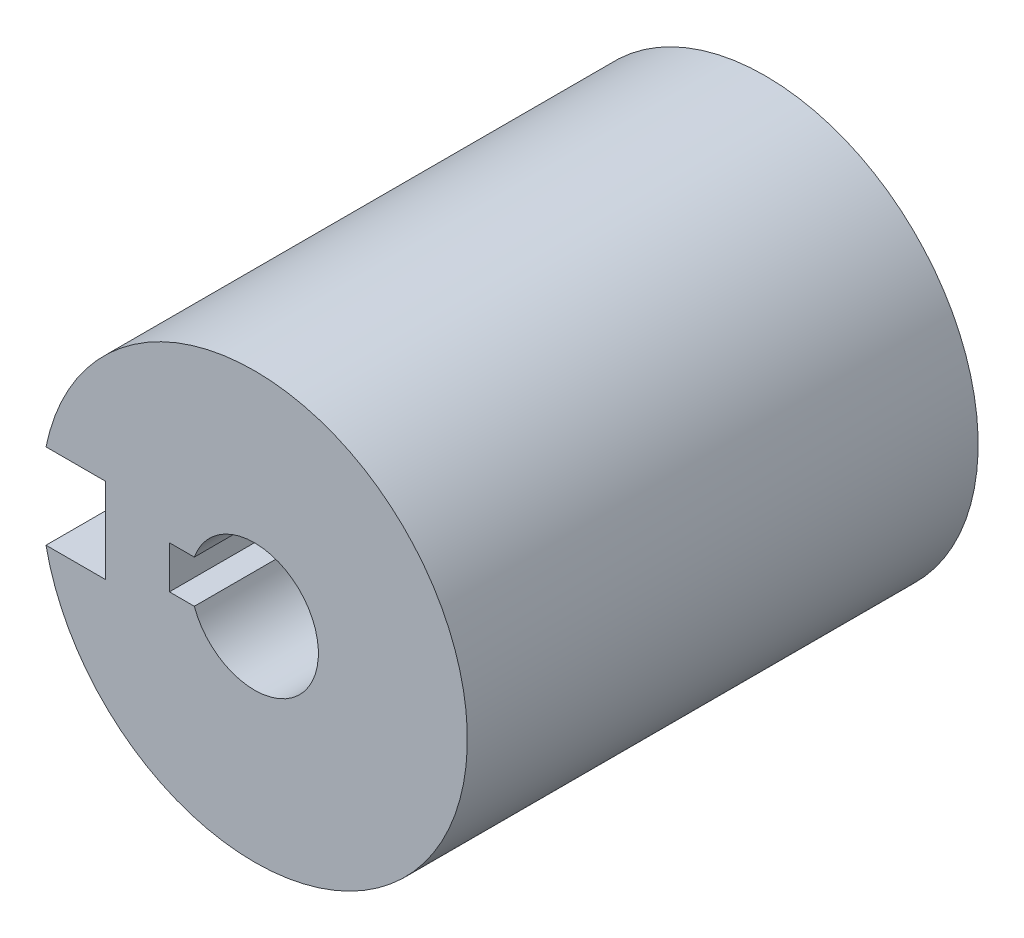
SolidWorks part; units mm, degrees
ref_plane "Front Plane" through (0, 0, 0) normal (0, 0, 1) x (1, 0, 0)
ref_plane "Top Plane" through (0, 0, 0) normal (0, 1, 0) x (1, 0, 0)
ref_plane "Right Plane" through (0, 0, 0) normal (1, 0, 0) x (0, 0, -1)
sketch "Sketch5" plane through (0, 0, 0) normal (0, 0, 1) x (1, 0, 0)
  circle A0 centre (0, 0) radius 5
  circle A1 centre (0, 0) radius 1.5
  dimension "D1" = 10
  dimension "D2" = 3
extrude "Boss-Extrude2" add sketch "Sketch5" along normal blind 12
sketch "Sketch6" plane through (0, 0, 12) normal (0, 0, 1) x (1, 0, 0)
  line L1 (-2, 0.5) -> (-1, 0.5)
  line L2 (-2, 0.5) -> (-2, -0.5)
  line L3 (-2, -0.5) -> (-1, -0.5)
  line L4 (-1, 0.5) -> (-1, -0.5)
  line L5 (-2, 0.5) -> (-1, -0.5) construction
  line L6 (-2, -0.5) -> (-1, 0.5) construction
  circle A0 centre (0, 0) radius 1.5 construction
  point P0 (-1.5, 0)
  dimension "D1" = 1
  dimension "D2" = 1
extrude "Cut-Extrude4" cut sketch "Sketch6" against normal blind 12
sketch "Sketch7" plane through (0, 0, 12) normal (0, 0, 1) x (1, 0, 0)
  line L1 (-5.5, 0.5) -> (-4.5, 0.5)
  line L2 (-5.5, 0.5) -> (-5.5, -0.5)
  line L3 (-5.5, -0.5) -> (-4.5, -0.5)
  line L4 (-4.5, 0.5) -> (-4.5, -0.5)
  line L5 (-5.5, 0.5) -> (-4.5, -0.5) construction
  line L6 (-5.5, -0.5) -> (-4.5, 0.5) construction
  circle A0 centre (0, 0) radius 5 construction
  point P0 (-5, 0)
  dimension "D1" = 1
  dimension "D2" = 1
extrude "Cut-Extrude6" cut sketch "Sketch7" against normal blind 4
sketch "Sketch8" plane through (0, 0, 0) normal (0, 0, -1) x (-1, 0, 0)
  line L1 (3.5, 1) -> (6.5, 1)
  line L2 (3.5, 1) -> (3.5, -1)
  line L3 (3.5, -1) -> (6.5, -1)
  line L4 (6.5, 1) -> (6.5, -1)
  line L5 (3.5, 1) -> (6.5, -1) construction
  line L6 (3.5, -1) -> (6.5, 1) construction
  circle A0 centre (0, 0) radius 5 construction
  point P0 (5, 0)
  dimension "D1" = 3
  dimension "D2" = 2
extrude "Cut-Extrude7" cut sketch "Sketch8" against normal blind 15
